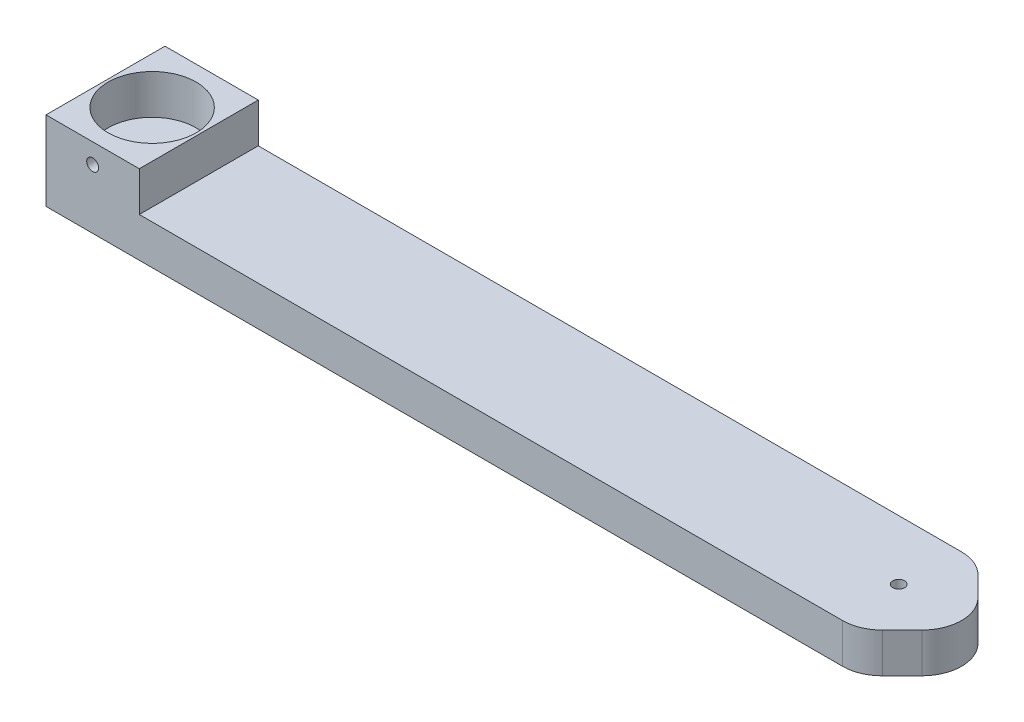
SolidWorks part; units mm, degrees
ref_plane "Front Plane" through (0, 0, 0) normal (0, 0, 1) x (1, 0, 0)
ref_plane "Top Plane" through (0, 0, 0) normal (0, 1, 0) x (1, 0, 0)
ref_plane "Right Plane" through (0, 0, 0) normal (1, 0, 0) x (0, 0, -1)
sketch "Sketch1" plane through (0, 0, 0) normal (0, 1, 0) x (1, 0, 0)
  line L1 (-110, -15) -> (110, -15)
  line L2 (-110, -15) -> (-110, 15)
  line L3 (-110, 15) -> (110, 15)
  line L4 (110, -15) -> (110, 15)
  line L5 (-110, -15) -> (110, 15) construction
  line L6 (-110, 15) -> (110, -15) construction
  point P0 (0, 0)
  dimension "D1" = 220
  dimension "D2" = 30
extrude "Boss-Extrude1" add sketch "Sketch1" along normal blind 10
sketch "Sketch2" plane through (0, 10, 0) normal (0, 1, 0) x (1, 0, 0)
  line L0 (-11, 0) -> (11, 0) construction
  line L2 (-86.4763, -15) -> (-110, -15)
  line L3 (-86.4763, -15) -> (-86.4763, 15)
  line L4 (-86.4763, 15) -> (-110, 15)
  line L5 (-110, -15) -> (-110, 15)
  line L6 (-86.4763, -15) -> (-110, 15) construction
  line L7 (-86.4763, 15) -> (-110, -15) construction
  circle A1 centre (-98.2382, 0) radius 11.1
  line M3 (110, 15) -> (-110, 15)
  line M4 (-110, 15) -> (-110, -15)
  line M5 (-110, -15) -> (110, -15)
  dimension "D2" = 22.2
extrude "Boss-Extrude3" add sketch "Sketch2" along normal blind 10 contours L3 A1 M5 M3 M4
sketch "Sketch4" plane through (0, 10, 0) normal (0, 1, 0) x (1, 0, 0)
  line L0 (-11, 0) -> (11, 0) construction
  line L1 (110, -15) -> (110, 15) construction
  circle A0 centre (90, 0) radius 4
  dimension "D1" = 8
  dimension "D2" = 20
sketch "Sketch6" plane through (0, 0, 15) normal (0, 0, 1) x (1, 0, 0)
  line L0 (-86.4763, 10) -> (-110, 10) construction
  line L1 (-110, 20) -> (-110, 0) construction
  line L2 (-98.2382, 20) -> (-98.2382, 10) construction
  line L3 (-110, 20) -> (-86.4763, 20) construction
  circle A0 centre (-98.2382, 15) radius 1.5
  dimension "D1" = 3
extrude "Cut-Extrude2" cut sketch "Sketch6" against normal blind 10
extrude "Cut-Extrude3" cut sketch "Sketch4" along normal blind 4 from surface at -10 starting at face at (0, 0, 0)
sketch "Sketch7" plane through (0, 4, 0) normal (0, -1, 0) x (-1, 0, 0)
  circle A0 centre (-90, 0) radius 1.5
  dimension "D1" = 3
extrude "Cut-Extrude4" cut sketch "Sketch7" against normal blind 14
sketch "Sketch8" plane through (0, 10, 0) normal (0, 1, 0) x (1, 0, 0)
  line L0 (95, 15) -> (110, 0)
  line L1 (110, 15) -> (-86.4763, 15) construction
  line L2 (110, -15) -> (110, 15) construction
  line L4 (110, 0) -> (95, -15)
  line L5 (-86.4763, -15) -> (110, -15) construction
  line L6 (95, -15) -> (110, -15)
  line L7 (110, -15) -> (110, 0)
  line L8 (110, 0) -> (110, 15)
  line L9 (110, 15) -> (95, 15)
  line L11 (110, 15) -> (95, 15) construction
  line L12 (110, 15) -> (110, 0) construction
  line L13 (110, 0) -> (95, 0) construction
  line L14 (95, 15) -> (95, 0) construction
  line M11 (-86.4763, -15) -> (110, -15)
  line M12 (110, -15) -> (110, 15)
  line M13 (110, 15) -> (-86.4763, 15)
extrude "Cut-Extrude5" cut sketch "Sketch8" against normal blind 10 contours L4 M12 M11 | L0 M13 M12
fillet "Fillet1" radius 10 3 edges at (95, 5, -15) (110, 5, 0) (95, 5, 15)
